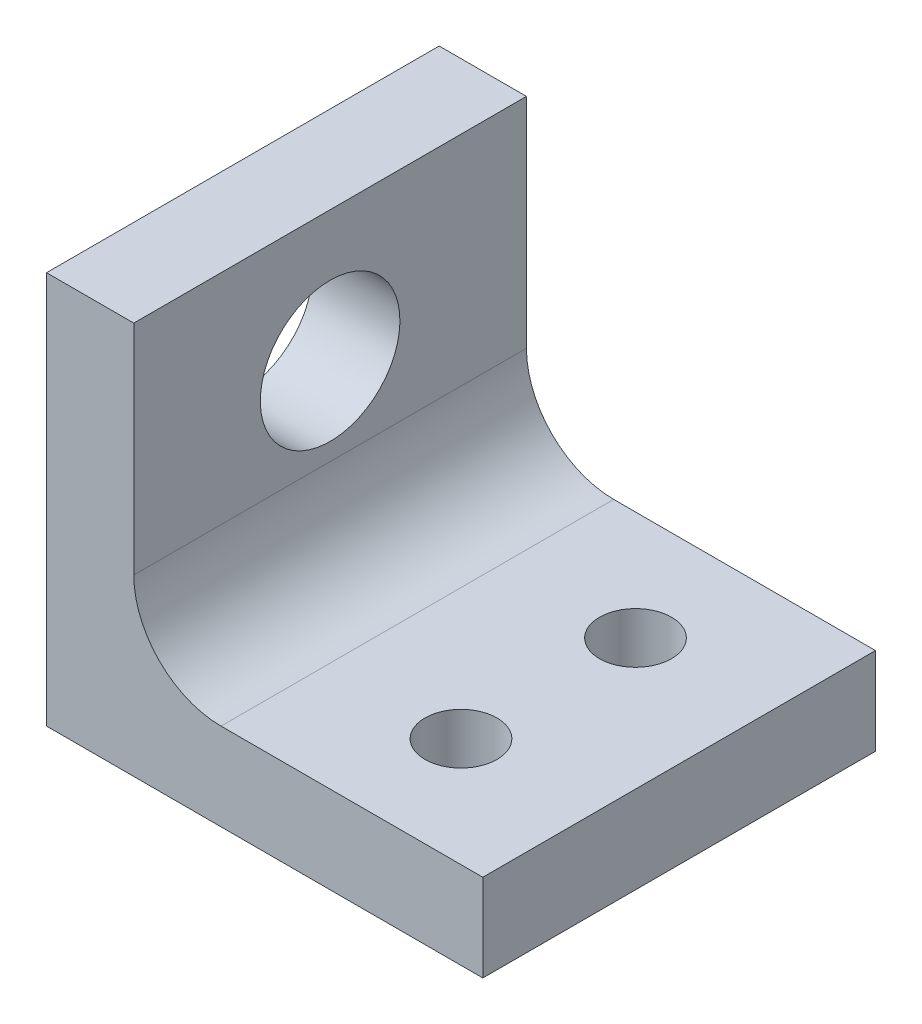
SolidWorks part; units mm, degrees
ref_plane "Front Plane" through (0, 0, 0) normal (0, 0, 1) x (1, 0, 0)
ref_plane "Top Plane" through (0, 0, 0) normal (0, 1, 0) x (1, 0, 0)
ref_plane "Right Plane" through (0, 0, 0) normal (1, 0, 0) x (0, 0, -1)
sketch "Sketch1" plane through (0, 0, 0) normal (0, 0, 1) x (1, 0, 0)
  line L0 (0, 0) -> (0, 18)
  line L1 (0, 18) -> (4, 18)
  line L2 (4, 18) -> (4, 4)
  line L3 (4, 4) -> (20, 4)
  line L4 (20, 4) -> (20, 0)
  line L5 (20, 0) -> (0, 0)
  dimension "D1" = 18
  dimension "D2" = 20
  dimension "D3" = 4
  dimension "D4" = 4
extrude "Boss-Extrude1" add sketch "Sketch1" along normal blind 18
sketch "Sketch2" plane through (4, 0, 0) normal (1, 0, 0) x (0, 0, -1)
  line L0 (-18, 18) -> (0, 18) construction
  circle A0 centre (-9, 12) radius 3.2
  point P4 (-9, 18)
  point P5 (0, 0)
  point P9 (-9, 12.5908)
  dimension "D1" = 6.4
  dimension "D2" = 6
extrude "Cut-Extrude1" cut sketch "Sketch2" against normal blind 25
fillet "Fillet1" radius 4 1 edges at (4, 4, 9)
sketch "Sketch3" plane through (0, 4, 0) normal (0, 1, 0) x (1, 0, 0)
  line L0 (14, 0) -> (14, -18) construction
  line L1 (20, 0) -> (8, 0) construction
  line L2 (20, -18) -> (8, -18) construction
  circle A0 centre (14, -5) radius 1.65
  circle A1 centre (14, -13) radius 1.65
  point P4 (13.5, -3.5493)
  point P11 (13.5, -13.6168)
  dimension "D1" = 3.3
  dimension "D2" = 3.3
  dimension "D3" = 5
  dimension "D4" = 5
extrude "Cut-Extrude2" cut sketch "Sketch3" against normal blind 25
equation "\"D4@Sketch1\"=\"D3@Sketch1\""
